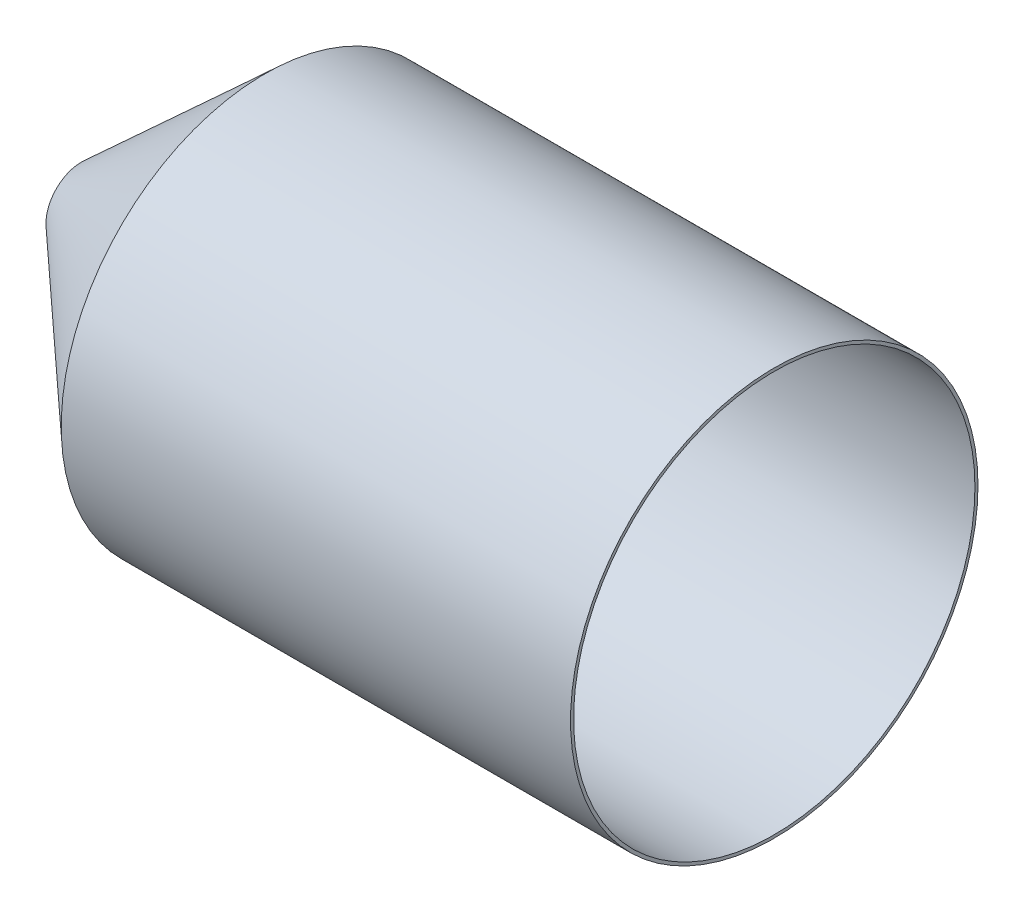
SolidWorks part; units mm, degrees
material "AISI 304"
ref_plane "Front Plane" through (0, 0, 0) normal (0, 0, 1) x (1, 0, 0)
ref_plane "Top Plane" through (0, 0, 0) normal (0, 1, 0) x (1, 0, 0)
ref_plane "Right Plane" through (0, 0, 0) normal (1, 0, 0) x (0, 0, -1)
sketch "Sketch1" plane through (0, 0, 0) normal (1, 0, 0) x (0, 0, -1)
  circle A0 centre (0, 0) radius 200
  circle A1 centre (0, 0) radius 197
  dimension "D1" = 400
  dimension "D2" = 3
extrude "Boss-Extrude1" add sketch "Sketch1" along normal blind 500
sketch "Sketch2" plane through (0, 0, 0) normal (1, 0, 0) x (0, 0, -1)
  circle A0 centre (0, 0) radius 200
ref_plane "Plane1" through (-180, 0, 0) normal (1, 0, 0) x (0, 0, -1)
sketch "Sketch3" plane through (-180, 0, 0) normal (1, 0, 0) x (0, 0, -1)
  circle A0 centre (0, 0) radius 35
surface "Surface-Loft1"
